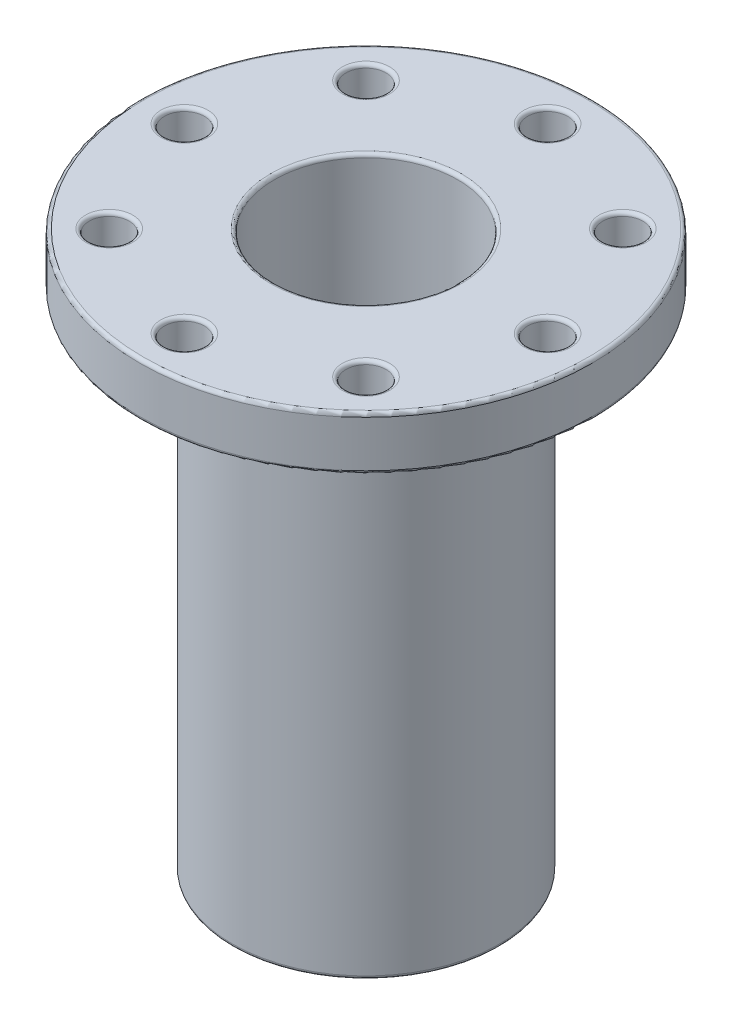
SolidWorks part; units mm, degrees
ref_plane "Front Plane" through (0, 0, 0) normal (0, 0, 1) x (1, 0, 0)
ref_plane "Top Plane" through (0, 0, 0) normal (0, 1, 0) x (1, 0, 0)
ref_plane "Right Plane" through (0, 0, 0) normal (1, 0, 0) x (0, 0, -1)
sketch "Sketch1" plane through (0, 0, 0) normal (0, 1, 0) x (1, 0, 0)
  line L0 (0, 0) -> (0, 20.4) construction
  circle A0 centre (0, 0) radius 25.4
  circle A1 centre (0, 20.4) radius 2.25
  circle A2 centre (14.425, 14.425) radius 2.25
  circle A3 centre (20.4, 0) radius 2.25
  circle A4 centre (14.425, -14.425) radius 2.25
  circle A5 centre (0, -20.4) radius 2.25
  circle A6 centre (-14.425, -14.425) radius 2.25
  circle A7 centre (-20.4, 0) radius 2.25
  circle A8 centre (-14.425, 14.425) radius 2.25
  point P5 (26.1735, 23.8865)
  point P6 (0, 0)
  point P22 (0, 0)
  dimension "D1" = 50.8
  dimension "D2" = 4.5
  dimension "D3" = 20.4
  dimension "D4" = 8
extrude "Boss-Extrude1" add sketch "Sketch1" along normal blind 6
sketch "Sketch2" plane through (0, 6, 0) normal (0, 1, 0) x (1, 0, 0)
  circle A0 centre (0, 0) radius 15
  dimension "D1" = 30
extrude "Boss-Extrude2" add sketch "Sketch2" against normal blind 62.5
sketch "Sketch3" plane through (0, 6, 0) normal (0, 1, 0) x (1, 0, 0)
  circle A0 centre (0, 0) radius 10.3125
  dimension "D1" = 20.625
extrude "Cut-Extrude1" cut sketch "Sketch3" against normal blind 38.1
sketch "Sketch4" plane through (0, -56.5, 0) normal (0, -1, 0) x (1, 0, 0)
  circle A0 centre (0, 0) radius 7.07
  dimension "D1" = 14.14
extrude "Cut-Extrude2" cut sketch "Sketch4" against normal through all
fillet "Fillet1" radius 0.4 24 edges at (-14.425, 6, -12.175) (-14.425, 6, 16.675) (14.425, 6, 16.675) (14.425, 6, -12.175) (0, 6, 25.4) (0, 6, -18.15) (20.4, 6, 2.25) (0, 6, 22.65) (-20.4, 6, 2.25) (-14.425, 0, -12.175) (-20.4, 0, 2.25) (-14.425, 0, 16.675) (0, 0, 22.65) (14.425, 0, 16.675) (20.4, 0, 2.25) (14.425, 0, -12.175) (0, 0, -18.15) (0, 0, 25.4) (0, 0, 15) (0, -56.5, 15) (0, -56.5, -7.07) (0, -32.1, 7.07) (0, 6, 10.3125) (0, -32.1, 10.3125)
